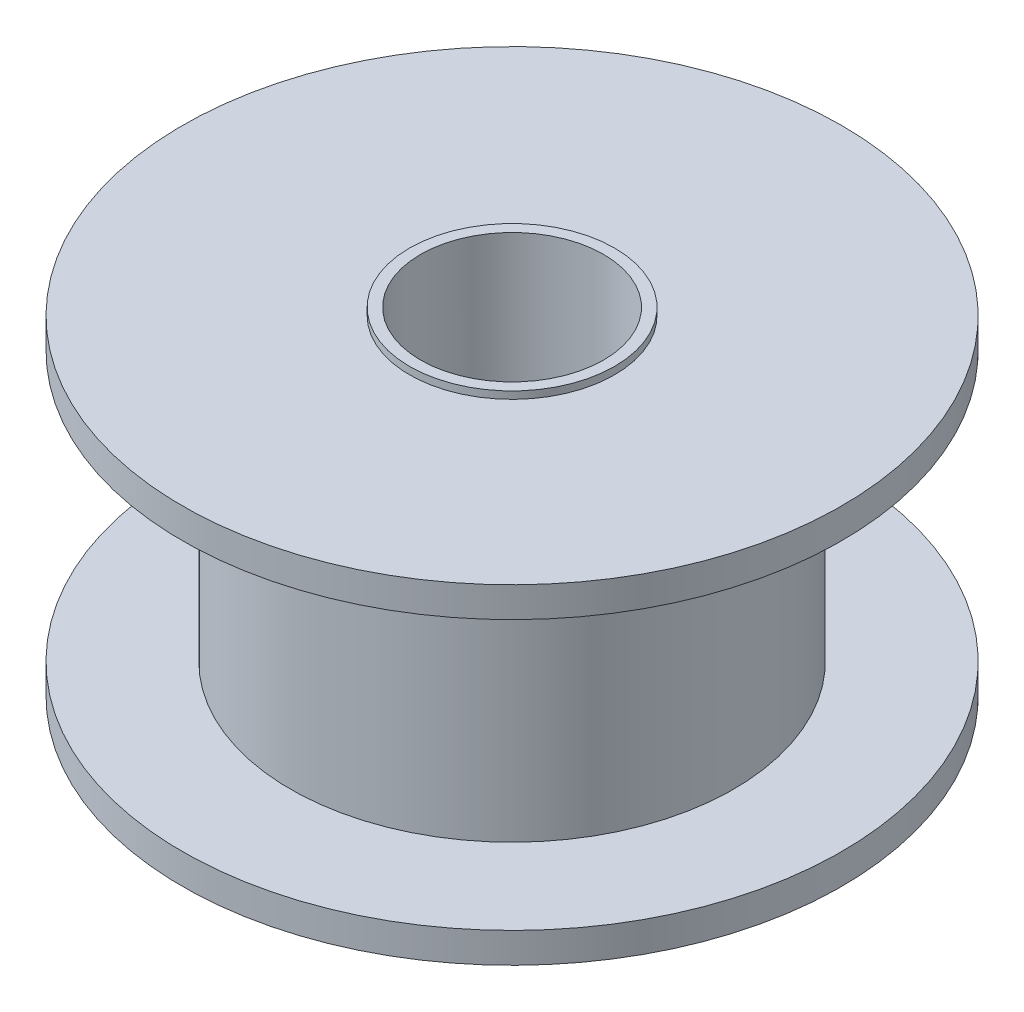
SolidWorks part; units mm, degrees
material "3003 Alloy"
ref_plane "Plano frontal" through (0, 0, 0) normal (0, 0, 1) x (1, 0, 0)
ref_plane "Plano superior" through (0, 0, 0) normal (0, 1, 0) x (1, 0, 0)
ref_plane "Plano direito" through (0, 0, 0) normal (1, 0, 0) x (0, 0, -1)
sketch "Esboço1" plane through (0, 0, 0) normal (0, 0, 1) x (1, 0, 0)
  line L0 (-9, -4.5) -> (-9, -3.675)
  line L1 (-9, -3.675) -> (-6.05, -3.675)
  line L2 (-6.05, -3.675) -> (-6.05, 3.675)
  line L3 (-6.05, 3.675) -> (-9, 3.675)
  line L4 (-9, 3.675) -> (-9, 4.5)
  line L5 (-9, 4.5) -> (-2.5, 4.5)
  line L6 (-2.5, 4.5) -> (-2.5, -4.5)
  line L7 (-2.5, -4.5) -> (-9, -4.5)
  line L8 (0, 0) -> (0, 32.5066) construction
  line L9 (-2.5, 0) -> (-6.05, 0) construction
  point P14 (-2.5, 0)
  dimension "D1" = 6.05
  dimension "D2" = 2.5
  dimension "D3" = 9
  dimension "D4" = 7.35
  dimension "D5" = 9
revolve "Revolução1" add sketch "Esboço1" angle 360 about L8
sketch "Esboço2" plane through (0, 4.5, 0) normal (0, 1, 0) x (1, 0, 0)
  circle A0 centre (0, 0) radius 2.5
  circle A1 centre (0, 0) radius 2.5 construction
  circle A2 centre (0, 0) radius 2.8
  dimension "D1" = 0.3
extrude "Ressalto-extrusão1" add sketch "Esboço2" along normal blind 0.2
sketch "Esboço4" plane through (0, -4.5, 0) normal (0, -1, 0) x (1, 0, 0)
  circle A0 centre (0, 0) radius 2.5
  circle A1 centre (0, 0) radius 2.8
  dimension "D1" = 0.3
extrude "Ressalto-extrusão2" add sketch "Esboço4" along normal blind 0.2
